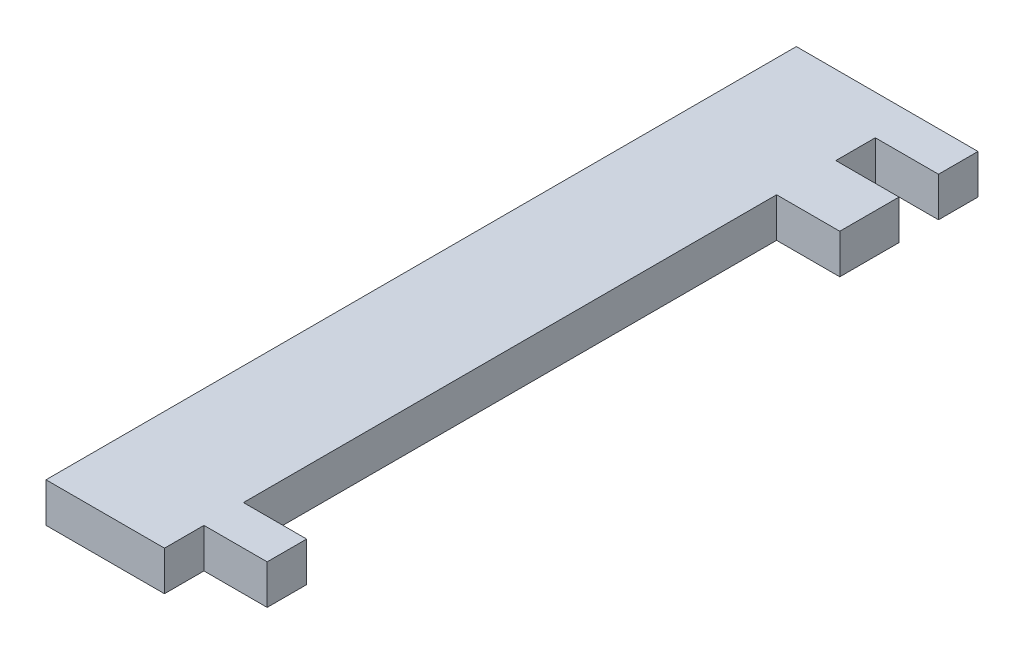
SolidWorks part; units mm, degrees
ref_plane "Alzado" through (0, 0, 0) normal (0, 0, 1) x (1, 0, 0)
ref_plane "Planta" through (0, 0, 0) normal (0, 1, 0) x (1, 0, 0)
ref_plane "Vista lateral" through (0, 0, 0) normal (1, 0, 0) x (0, 0, -1)
sketch "Croquis1" plane through (0, 0, 0) normal (0, 0, 1) x (1, 0, 0)
  line L1 (-7.5, -2.5) -> (7.5, -2.5)
  line L2 (-7.5, -2.5) -> (-7.5, 2.5)
  line L3 (-7.5, 2.5) -> (7.5, 2.5)
  line L4 (7.5, -2.5) -> (7.5, 2.5)
  line L5 (-7.5, -2.5) -> (7.5, 2.5) construction
  line L6 (-7.5, 2.5) -> (7.5, -2.5) construction
  point P0 (0, 0)
  dimension "D1" = 15
  dimension "D2" = 5
extrude "Saliente-Extruir1" add sketch "Croquis1" along normal blind 90
sketch "Croquis2" plane through (0, 0, 0) normal (0, 0, -1) x (-1, 0, 0)
  line L1 (-7.5, 2.5) -> (-15.5, 2.5)
  line L3 (-7.5, -2.5) -> (-15.5, -2.5)
  line L4 (-7.5, 2.5) -> (-7.5, -2.5)
  line L5 (-7.5, -2.5) -> (7.5, -2.5)
  line L6 (7.5, -2.5) -> (7.5, 2.5)
  line L7 (7.5, 2.5) -> (-7.5, 2.5)
  line L9 (-7.5, -2.5) -> (7.5, -2.5)
  line L10 (7.5, -2.5) -> (7.5, 2.5)
  line L11 (7.5, 2.5) -> (-7.5, 2.5)
  line L12 (-15.5, 2.5) -> (-15.5, -2.5)
  dimension "D2" = 23
  dimension "D1" = 0
extrude "Saliente-Extruir2" add sketch "Croquis2" along normal blind 5
sketch "Croquis3" plane through (0, 2.5, 0) normal (0, 1, 0) x (1, 0, 0)
  line L0 (-7.5, -90) -> (-7.5, 5) construction
  line L1 (-7.5, -5) -> (15.5, -5)
  line L2 (-7.5, -5) -> (-7.5, -12.5)
  line L3 (-7.5, -12.5) -> (15.5, -12.5)
  line L4 (15.5, -5) -> (15.5, -12.5)
  line L5 (-7.5, 5) -> (15.5, 5) construction
  line L7 (35.499, -85) -> (-7.4432, -85) construction
  line L8 (-7.5, -85) -> (15.5, -85)
  line L9 (-7.5, -85) -> (-7.5, -80)
  line L10 (-7.5, -80) -> (15.5, -80)
  line L11 (15.5, -85) -> (15.5, -80)
  dimension "D1" = 10
  dimension "D2" = 7.5
  dimension "D3" = 23
  dimension "D4" = 23
  dimension "D5" = 0
  dimension "D6" = 5
extrude "Saliente-Extruir3" add sketch "Croquis3" against normal blind 5
